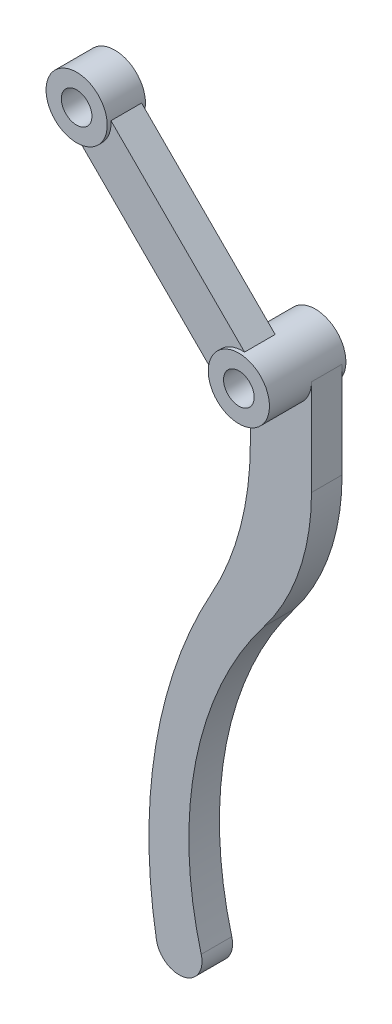
SolidWorks part; units mm, degrees
ref_plane "前视基准面" through (0, 0, 0) normal (0, 0, 1) x (1, 0, 0)
ref_plane "上视基准面" through (0, 0, 0) normal (0, 1, 0) x (1, 0, 0)
ref_plane "右视基准面" through (0, 0, 0) normal (1, 0, 0) x (0, 0, -1)
sketch "草图1" plane through (0, 0, 0) normal (0, 0, 1) x (1, 0, 0)
  line L0 (-42.4264, 42.4264) -> (0, 0) construction
  line L1 (0, 0) -> (0, 41.7706) construction
  circle A0 centre (0, 0) radius 8
  circle A1 centre (0, 0) radius 4
  circle A2 centre (-42.4264, 42.4264) radius 4
  circle A3 centre (-42.4264, 42.4264) radius 8
  dimension "D1" = 16
  dimension "D2" = 8
  dimension "D3" = 60
  dimension "D4" = 45
extrude "凸台-拉伸1" add sketch "草图1" along normal blind 10
sketch "草图2" plane through (0, 0, 0) normal (0, 0, 1) x (1, 0, 0)
  line L0 (-42.4264, 42.4264) -> (0, 0) construction
  line L1 (-42.9274, 34.4421) -> (-7.9843, -0.501)
  line L2 (-34.4421, 42.9274) -> (0.501, 7.9843)
  line L4 (-38.1838, 46.669) -> (4.2426, 4.2426) construction
  line L5 (-46.669, 38.1838) -> (-4.2426, -4.2426) construction
  circle A0 centre (0, 0) radius 8 construction
  circle A1 centre (-42.4264, 42.4264) radius 8 construction
  arc A2 (0.501, 7.9843) -> (-7.9843, -0.501) centre (0, 0) ccw
  arc A3 (-42.9274, 34.4421) -> (-34.4421, 42.9274) centre (-42.4264, 42.4264) ccw
  dimension "D1" = 6
  dimension "D2" = 6
extrude "凸台-拉伸2" add sketch "草图2" along normal blind 8 from offset 1
sketch "草图3" plane through (0, 0, 0) normal (0, 0, 1) x (1, 0, 0)
  line L0 (-8, 0) -> (-8, -22)
  line L1 (8, 0) -> (8, -25.0756)
  line L2 (-26.6397, -145.6407) -> (70.9188, -119.5) construction
  line L3 (70.9188, -119.5) -> (70.9188, -68.7814) construction
  arc A0 (-8, -22) -> (-18.1016, -60.913) centre (-88, -22) cw
  circle A1 centre (0, 0) radius 8
  arc A2 (-8, 0) -> (8, 0) centre (0, 0) ccw
  arc A3 (-18.1016, -60.913) -> (-32.5489, -146.6808) centre (95.4832, -124.1466) ccw
  arc A4 (-32.5489, -146.6808) -> (-20.8442, -144.0878) centre (-26.6397, -145.6407) ccw
  arc A5 (-20.8442, -144.0878) -> (-4.4185, -61.627) centre (70.9188, -119.5) cw
  arc A6 (-4.4185, -61.627) -> (8, -25.0756) centre (-52, -25.0756) ccw
  dimension "D3" = 80
  dimension "D4" = 60
  dimension "D5" = 95
  dimension "D6" = 130
  dimension "D7" = 6
  dimension "D10" = 10
  dimension "D2" = 22
  dimension "D8" = 119.5
  dimension "D9" = 105
  dimension "D1" = 0
extrude "凸台-拉伸3" add sketch "草图3" against normal blind 8 from offset 1 offset against normal yes
sketch "草图4" plane through (0, 0, 0) normal (0, 0, 1) x (1, 0, 0)
  circle A0 centre (0, 0) radius 4 construction
  circle A1 centre (0, 0) radius 8 construction
  circle A2 centre (0, 0) radius 4
  circle A3 centre (0, 0) radius 8
extrude "凸台-拉伸4" add sketch "草图4" against normal blind 10
